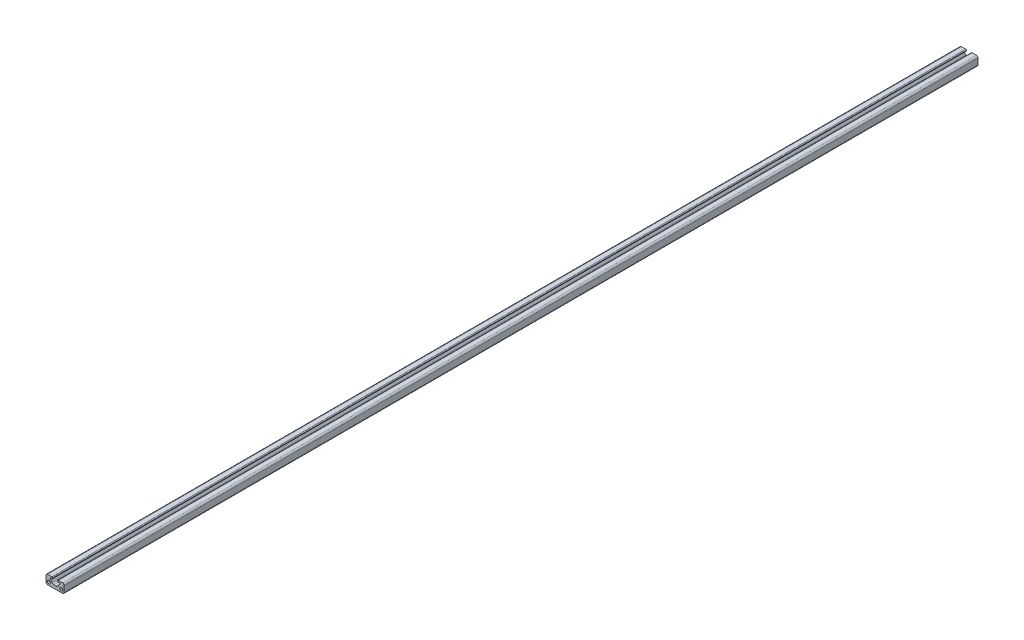
SolidWorks part; units mm, degrees
ref_plane "Front Plane" through (0, 0, 0) normal (0, 0, 1) x (1, 0, 0)
ref_plane "Top Plane" through (0, 0, 0) normal (0, 1, 0) x (1, 0, 0)
ref_plane "Right Plane" through (0, 0, 0) normal (1, 0, 0) x (0, 0, -1)
sketch "Sketch1" plane through (0, 0, 0) normal (0, 0, 1) x (1, 0, 0)
  line L5 (3.25, -1.87) -> (-3.25, -1.87)
  line L6 (12.5, 6.25) -> (-12.5, 6.25)
  line L10 (12.5, 6.25) -> (12.5, -6.25)
  line L11 (12.5, -6.25) -> (-12.5, -6.25)
  line L12 (-12.5, 6.25) -> (-12.5, -6.25)
  line L13 (12.5, 6.25) -> (-12.5, -6.25) construction
  line L14 (12.5, -6.25) -> (-12.5, 6.25) construction
  line L15 (7.345, 3.97) -> (-7.345, 3.97)
  line L16 (3.25, 6.25) -> (3.25, 3.97)
  line L17 (-3.25, 6.25) -> (-3.25, 3.97)
  line L18 (7.345, 3.97) -> (3.25, -1.87)
  line L19 (-3.25, -1.87) -> (-7.345, 3.97)
  circle A0 centre (-8.5, -2.25) radius 2
  circle A1 centre (8.5, -2.25) radius 2
  point P0 (0, 0)
  dimension "D3" = 4
  dimension "D4" = 4
  dimension "D1" = 25
  dimension "D2" = 12.5
  dimension "D5" = 4
  dimension "D6" = 4
  dimension "D7" = 17
  dimension "D8" = 6.5
  dimension "D9" = 14.69
  dimension "D10" = 6.5
  dimension "D11" = 9.25
  dimension "D12" = 5.155
  dimension "D13" = 9.25
  dimension "D14" = 5.84
  dimension "D15" = 8.12
extrude "Boss-Extrude2" add sketch "Sketch1" along normal blind 1257.3 contours L5 L19 L15 L17 L6 L12 L11 L10 L16 L18 A1 A0
fillet "Fillet1" radius 1.065 4 edges at (-3.25, 3.97, 628.65) (-3.25, 6.25, 628.65) (3.25, 3.97, 628.65) (3.25, 6.25, 628.65)
fillet "Fillet4" radius 2.13 1 edges at (12.5, 6.25, 628.65)
fillet "Fillet5" radius 2.13 3 edges at (12.5, -6.25, 628.65) (-12.5, -6.25, 628.65) (-12.5, 6.25, 628.65)
fillet "Fillet8" radius 0.5325 1 edges at (7.345, 3.97, 628.65)
fillet "Fillet11" radius 0.5325 1 edges at (-7.345, 3.97, 628.65)
fillet "Fillet15" radius 3 1 edges at (-3.25, -1.87, 628.65)
fillet "Fillet16" radius 3 1 edges at (3.25, -1.87, 628.65)
